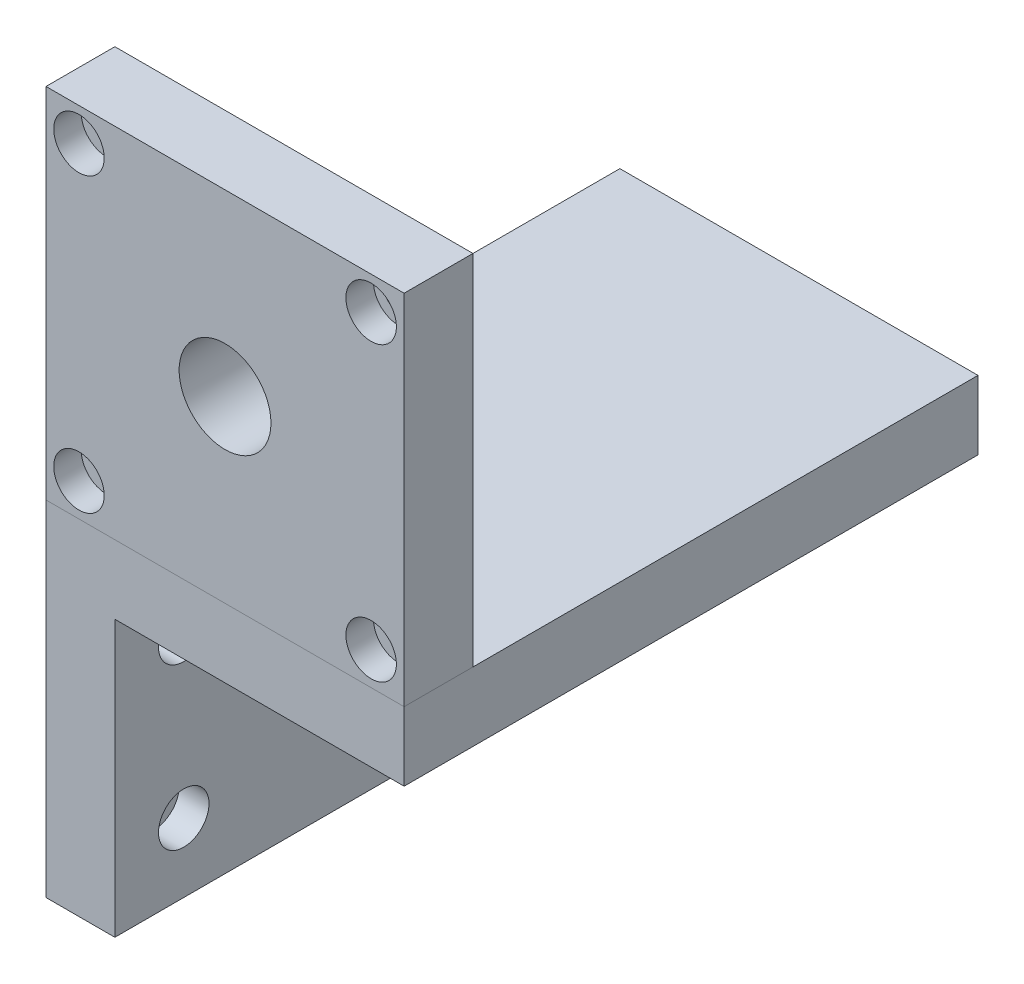
SolidWorks part; units mm, degrees
ref_plane "前视基准面" through (0, 0, 0) normal (0, 0, 1) x (1, 0, 0)
ref_plane "上视基准面" through (0, 0, 0) normal (0, 1, 0) x (1, 0, 0)
ref_plane "右视基准面" through (0, 0, 0) normal (1, 0, 0) x (0, 0, -1)
sketch "草图1" plane through (0, 0, 0) normal (0, 0, 1) x (1, 0, 0)
  line L1 (0, 0) -> (78, 0)
  line L2 (0, 0) -> (0, 78)
  line L3 (0, 78) -> (78, 78)
  line L4 (78, 0) -> (78, 78)
  dimension "D1" = 78
  dimension "D2" = 78
extrude "凸台-拉伸1" add sketch "草图1" along normal blind 15
sketch "草图2" plane through (0, 0, 0) normal (0, -1, 0) x (1, 0, 0)
  line L1 (0, 15) -> (78, 15)
  line L2 (0, 15) -> (0, -110)
  line L3 (0, -110) -> (78, -110)
  line L4 (78, 15) -> (78, -110)
  dimension "D1" = 125
  dimension "D2" = 78
extrude "凸台-拉伸2" add sketch "草图2" along normal blind 15 separate body
sketch "草图3" plane through (0, -15, 0) normal (0, -1, 0) x (1, 0, 0)
  line L0 (0, -110) -> (78, -110) construction
  line L1 (0, 15) -> (15, 15)
  line L2 (0, 15) -> (0, -110)
  line L3 (0, -110) -> (15, -110)
  line L4 (15, 15) -> (15, -110)
  dimension "D1" = 15
extrude "凸台-拉伸3" add sketch "草图3" along normal blind 60
sketch "草图4" plane through (0, 0, 0) normal (0, 0, -1) x (-1, 0, 0)
  circle A0 centre (-70.8198, 70.8198) radius 3.0833
  circle A1 centre (-70.8198, 7.1802) radius 2.75
  circle A2 centre (-7.1802, 70.8198) radius 2.75
  circle A3 centre (-7.1802, 7.1802) radius 2.75
extrude "切除-拉伸1" cut sketch "草图4" against normal through all
sketch "草图5" plane through (0, 0, 15) normal (0, 0, 1) x (1, 0, 0)
  circle A0 centre (39, 39) radius 10
  dimension "D1" = 20
extrude "切除-拉伸2" cut sketch "草图5" against normal blind 60
sketch "草图6" plane through (0, 0, 15) normal (0, 0, 1) x (1, 0, 0)
  circle A0 centre (7.1802, 70.8198) radius 5.5
  circle A1 centre (7.1802, 7.1802) radius 5.5
  circle A2 centre (70.8198, 7.1802) radius 5.5
  circle A3 centre (70.8198, 70.8198) radius 5.5
  dimension "D1" = 11
  dimension "D2" = 11
  dimension "D3" = 11
  dimension "D4" = 11
extrude "切除-拉伸3" cut sketch "草图6" against normal blind 6
sketch "草图7" plane through (15, 0, 0) normal (1, 0, 0) x (0, 0, -1)
  line L0 (110, -75) -> (110, -15) construction
  line L1 (-15, -75) -> (-15, -15) construction
  line L2 (110, -75) -> (-15, -75) construction
  circle A0 centre (0, -25) radius 3.5
  circle A1 centre (95, -25) radius 3.5
  circle A2 centre (0, -60) radius 3.5
  circle A3 centre (95, -60) radius 3.5
  dimension "D1" = 7
  dimension "D2" = 7
  dimension "D3" = 7
  dimension "D4" = 7
  dimension "D5" = 15
  dimension "D6" = 15
  dimension "D7" = 15
  dimension "D8" = 15
  dimension "D9" = 15
  dimension "D10" = 15
  dimension "D11" = 35
  dimension "D12" = 35
extrude "切除-拉伸4" cut sketch "草图7" against normal through all
sketch "草图8" plane through (15, 0, 0) normal (1, 0, 0) x (0, 0, -1)
  circle A0 centre (0, -25) radius 5.5
  circle A1 centre (0, -60) radius 5.5
  circle A2 centre (95, -60) radius 5.5
  circle A3 centre (95, -25) radius 5.5
  dimension "D1" = 11
  dimension "D2" = 11
  dimension "D3" = 11
  dimension "D4" = 11
extrude "切除-拉伸5" cut sketch "草图8" against normal blind 6.5
